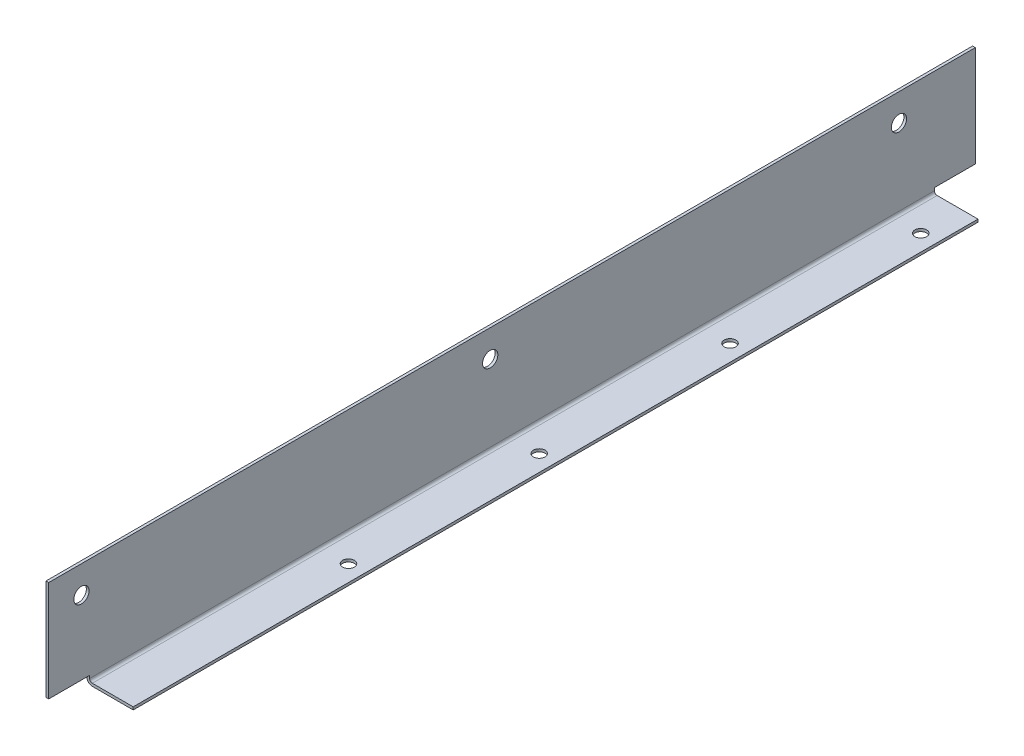
SolidWorks part; units mm, degrees
ref_plane "Спереди" through (0, 0, 0) normal (0, 0, 1) x (1, 0, 0)
ref_plane "Сверху" through (0, 0, 0) normal (0, 1, 0) x (1, 0, 0)
ref_plane "Справа" through (0, 0, 0) normal (1, 0, 0) x (0, 0, -1)
sketch "Эскиз1" plane through (0, 0, 0) normal (0, 0, 1) x (1, 0, 0)
  line L0 (0, 0) -> (0, 42.8354) construction
  line L1 (0, 0) -> (34, 0) construction
  line L2 (17, 0) -> (2, 0)
  line L3 (0, 2) -> (0, 40)
  line L4 (17, 1) -> (2, 1)
  line L5 (1, 2) -> (1, 40)
  line L6 (17, 1) -> (17, 0)
  line L7 (0, 40) -> (1, 40)
  arc A0 (2, 0) -> (0, 2) centre (2, 2) cw
  arc A1 (2, 1) -> (1, 2) centre (2, 2) cw
  dimension "D1" = 2
  dimension "D2" = 40
  dimension "D3" = 15
  dimension "D4" = 1
extrude "Вытянуть1" add sketch "Эскиз1" along normal blind 340
sketch "Эскиз2" plane through (0, 0, 0) normal (-1, 0, 0) x (0, 0, 1)
  line L0 (-10.0095, 30) -> (347.9915, 30) construction
  line L1 (340, 0) -> (0, 0) construction
  line L2 (0, 40) -> (0, 2) construction
  circle A0 centre (28, 30) radius 2.8
  circle A1 centre (178, 30) radius 2.8
  circle A2 centre (328, 30) radius 2.8
  dimension "D2" = 28
  dimension "D3" = 150
  dimension "D4" = 150
  dimension "D5" = 5.6
  dimension "D1" = 30
extrude "Вырез-Вытянуть1" cut sketch "Эскиз2" against normal blind 340
sketch "Эскиз3" plane through (0, 0, 0) normal (0, -1, 0) x (1, 0, 0)
  line L0 (11, 0) -> (11, 64.9266) construction
  line L1 (2, 0) -> (17, 0) construction
  line L2 (17, 340) -> (17, 0) construction
  circle A0 centre (11, 30) radius 2.15
  circle A1 centre (11, 100) radius 2.15
  circle A2 centre (11, 170) radius 2.15
  circle A3 centre (11, 240) radius 2.15
  dimension "D2" = 30
  dimension "D3" = 4.3
  dimension "D4" = 210
  dimension "D5" = 70
  dimension "D6" = 70
  dimension "D1" = 6
extrude "Вырез-Вытянуть2" cut sketch "Эскиз3" against normal blind 340
sketch "Эскиз4" plane through (0, 0, 0) normal (0, -1, 0) x (1, 0, 0)
  line L0 (2, 340) -> (17, 340) construction
  line L1 (-12.3496, 325) -> (25.2737, 325)
  line L2 (-12.3496, 325) -> (-12.3496, 345.6559)
  line L3 (-12.3496, 345.6559) -> (25.2737, 345.6559)
  line L4 (25.2737, 325) -> (25.2737, 345.6559)
  line L6 (-17.2738, 0) -> (25.2737, 0)
  line L7 (-17.2738, 0) -> (-17.2738, 15)
  line L8 (-17.2738, 15) -> (25.2737, 15)
  line L9 (25.2737, 0) -> (25.2737, 15)
  dimension "D1" = 15
  dimension "D2" = 15
extrude "Вырез-Вытянуть3" cut sketch "Эскиз4" against normal blind 3
